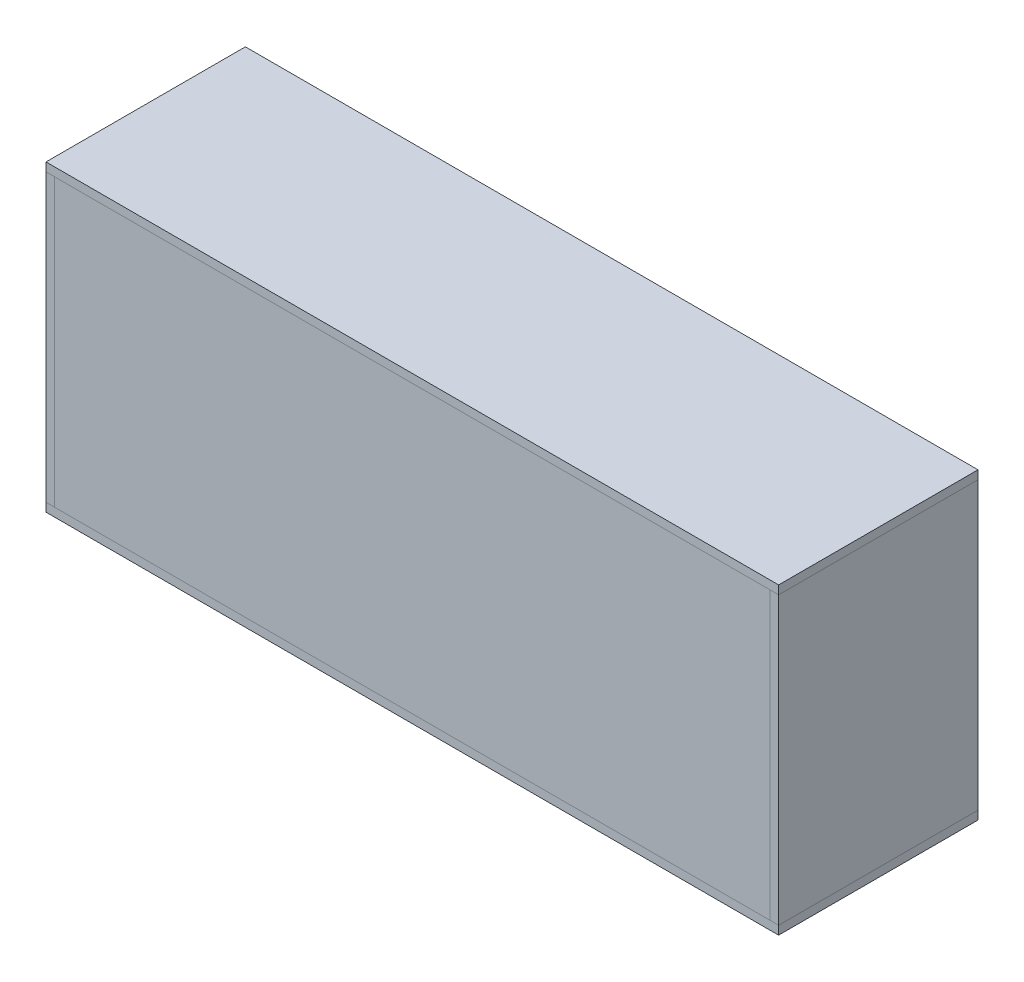
SolidWorks part; units mm, degrees
other "Marquage1"
sketch "Esquisse15" plane through (-404.4643, -5874.2293, 0) normal (-0.542, -0.1752, -0.8219) x (0.838, -0.1872, -0.5126)
ref_plane "Plan de face" through (0, 0, 0) normal (0, 0, 1) x (1, 0, 0)
ref_plane "Plan de dessus" through (0, 0, 0) normal (0, 1, 0) x (1, 0, 0)
ref_plane "Plan de droite" through (0, 0, 0) normal (1, 0, 0) x (0, 0, -1)
sketch "Esquisse1" plane through (0, 0, 0) normal (0, 1, 0) x (1, 0, 0)
  line L1 (-404.4643, 0) -> (1131.5357, 0)
  line L2 (-404.4643, 0) -> (-404.4643, -418)
  line L3 (-404.4643, -418) -> (1131.5357, -418)
  line L4 (1131.5357, 0) -> (1131.5357, -418)
  dimension "D1" = 1536
  dimension "D2" = 418
extrude "Boss.-Extru.1" add sketch "Esquisse1" along normal blind 18
sketch "Esquisse2" plane through (0, 0, 0) normal (0, -1, 0) x (1, 0, 0)
  line L0 (-386.4643, 418) -> (-386.4643, 0)
  line L1 (-404.4643, 418) -> (1131.5357, 418) construction
  line L2 (1131.5357, 0) -> (-404.4643, 0) construction
  line L3 (-404.4643, 0) -> (-404.4643, 418) construction
  line L4 (1113.5357, 418) -> (1113.5357, 0)
  line L5 (1131.5357, 418) -> (1131.5357, 0) construction
  dimension "D1" = 18
  dimension "D2" = 18
extrude "Extru.-Mince3" add sketch "Esquisse2" along normal blind 600 separate body thin contours L4
sketch "Esquisse6" plane through (0, 0, 0) normal (0, -1, 0) x (1, 0, 0)
  line L0 (-386.4643, 0) -> (-386.4643, 418)
  line L1 (1131.5357, 0) -> (-404.4643, 0) construction
  line L2 (-404.4643, 418) -> (1131.5357, 418) construction
  line L3 (-404.4643, 0) -> (-404.4643, 418) construction
  line L8 (1131.5357, 0) -> (1131.5357, 418)
  line L9 (1131.5357, 418) -> (-404.4643, 418)
  line L10 (-404.4643, 418) -> (-404.4643, 0)
  line L11 (-404.4643, 0) -> (1131.5357, 0)
  line L13 (1131.5357, 0) -> (1131.5357, 418)
  dimension "D1" = 18
  dimension "D2" = 0
extrude "Extru.-Mince4" add sketch "Esquisse6" along normal blind 600 separate body thin contours L0
sketch "Esquisse10" plane through (-386.4643, 0, 0) normal (1, 0, 0) x (0, 0, -1)
  line L0 (-400, -600) -> (-400, 0)
  line L1 (0, -600) -> (-418, -600) construction
  point P4 (0, 0)
  point P5 (-400.7138, 1.3906)
  point P9 (0, 0)
  point P10 (0, 0)
extrude "Extru.-Mince5" add sketch "Esquisse10" along normal blind 1500 separate body thin thin type one direction reverse wall 18
sketch "Esquisse11" plane through (-386.4643, 0, 0) normal (1, 0, 0) x (0, 0, -1)
  line L0 (-400, -150) -> (-300, -150)
  line L3 (-400, -600) -> (-400, 0) construction
  line L6 (-300, -150) -> (-300, -600)
  line L7 (0, -600) -> (-418, -600) construction
  dimension "D1" = 450
  dimension "D2" = 100
extrude "Extru.-Mince6" add sketch "Esquisse11" along normal blind 1500 separate body thin
sketch "Esquisse19" plane through (1113.5357, 0, 0) normal (-1, 0, 0) x (0, 0, 1)
  line L2 (400, -393) -> (318, -393)
  line L5 (318, -393) -> (318, -375)
  line L6 (318, -375) -> (400, -375)
  line L7 (400, -375) -> (400, -393)
  point P0 (805.9794, -152.1962)
  point P6 (0, 0)
  point P7 (0, 0)
  point P8 (760.8282, -71.941)
  point P10 (0, 0)
  dimension "D2" = 18
extrude "Boss.-Extru.4" add sketch "Esquisse19" along normal blind 1500 separate body
sketch "Esquisse12" plane through (-386.4643, 0, 0) normal (1, 0, 0) x (0, 0, -1)
  line L0 (0, -600) -> (0, -100)
  line L1 (0, -600) -> (0, 0) construction
  line L2 (0, -100) -> (-300, -100)
  point P5 (0, 0)
  point P7 (0, 0)
  point P8 (0, 0)
  dimension "D2" = 300
extrude "Extru.-Mince7" add sketch "Esquisse12" along normal blind 1500 separate body thin contours L0 L2 thin type one direction reverse wall 18
sketch "Esquisse13" plane through (0, 0, 0) normal (0, 0, -1) x (-1, 0, 0)
  line L0 (404.4643, 18) -> (404.4643, 0) construction
  line L1 (386.4643, -100) -> (386.4643, -600) construction
  line L2 (-1131.5357, 18) -> (-1131.5357, 0) construction
  line L3 (-1131.5357, -600) -> (-1113.5357, -600) construction
  line L4 (404.4643, -582) -> (-1131.5357, -582) construction
  line L5 (-1113.5357, -100) -> (-1113.5357, -600) construction
  line L6 (386.4643, -582) -> (-1113.5357, -100) construction
  line L7 (386.4643, -100) -> (-1113.5357, -582) construction
  circle A0 centre (-363.5357, -341) radius 181.9
  circle A1 centre (111.4143, -341) radius 181.9
  circle A2 centre (-838.4857, -341) radius 181.9
  point P15 (-363.5357, -341)
  point P17 (0, 0)
  point P18 (0, 0)
  point P25 (0, 0)
  point P26 (0, 0)
  point P27 (0, 0)
  point P28 (0, 0)
  dimension "D2" = 363.8
  dimension "D3" = 363.8
  dimension "D4" = 363.8
  dimension "D1" = 293.05
  dimension "D5" = 18
  dimension "D6" = 0
  dimension "D7" = 293.05
  dimension "D8" = 474.95
  dimension "D9" = 0
  dimension "D10" = 0
  dimension "D11" = 1500
extrude "Enlèv. mat.-Extru.1" cut sketch "Esquisse13" against normal blind 18
sketch "Esquisse14" plane through (0, -600, 0) normal (0, -1, 0) x (1, 0, 0)
  line L1 (-404.4643, 0) -> (1131.5357, 0)
  line L2 (-404.4643, 0) -> (-404.4643, 418)
  line L3 (-404.4643, 418) -> (1131.5357, 418)
  line L4 (1131.5357, 0) -> (1131.5357, 418)
extrude "Boss.-Extru.2" add sketch "Esquisse14" along normal blind 18 separate body contours L3 L4 L1 L2
sketch "Esquisse16" plane through (0, -100, 0) normal (0, 1, 0) x (1, 0, 0)
  line L0 (1113.5357, 0) -> (-386.4643, 0) construction
  line L1 (104.5357, 0) -> (122.5357, 0)
  line L2 (104.5357, 0) -> (104.5357, -300)
  line L3 (104.5357, -300) -> (122.5357, -300)
  line L4 (122.5357, 0) -> (122.5357, -300)
  line L5 (1113.5357, -300) -> (-386.4643, -300) construction
  line L6 (-386.4643, 0) -> (-386.4643, -300) construction
  line L7 (604.5357, 0) -> (622.5357, 0)
  line L8 (604.5357, 0) -> (604.5357, -300)
  line L9 (604.5357, -300) -> (622.5357, -300)
  line L10 (622.5357, 0) -> (622.5357, -300)
  line L11 (1113.5357, 0) -> (1113.5357, -300) construction
  dimension "D1" = 18
  dimension "D2" = 18
  dimension "D3" = 491
  dimension "D4" = 491
extrude "Boss.-Extru.3" add sketch "Esquisse16" along normal blind 100 separate body
